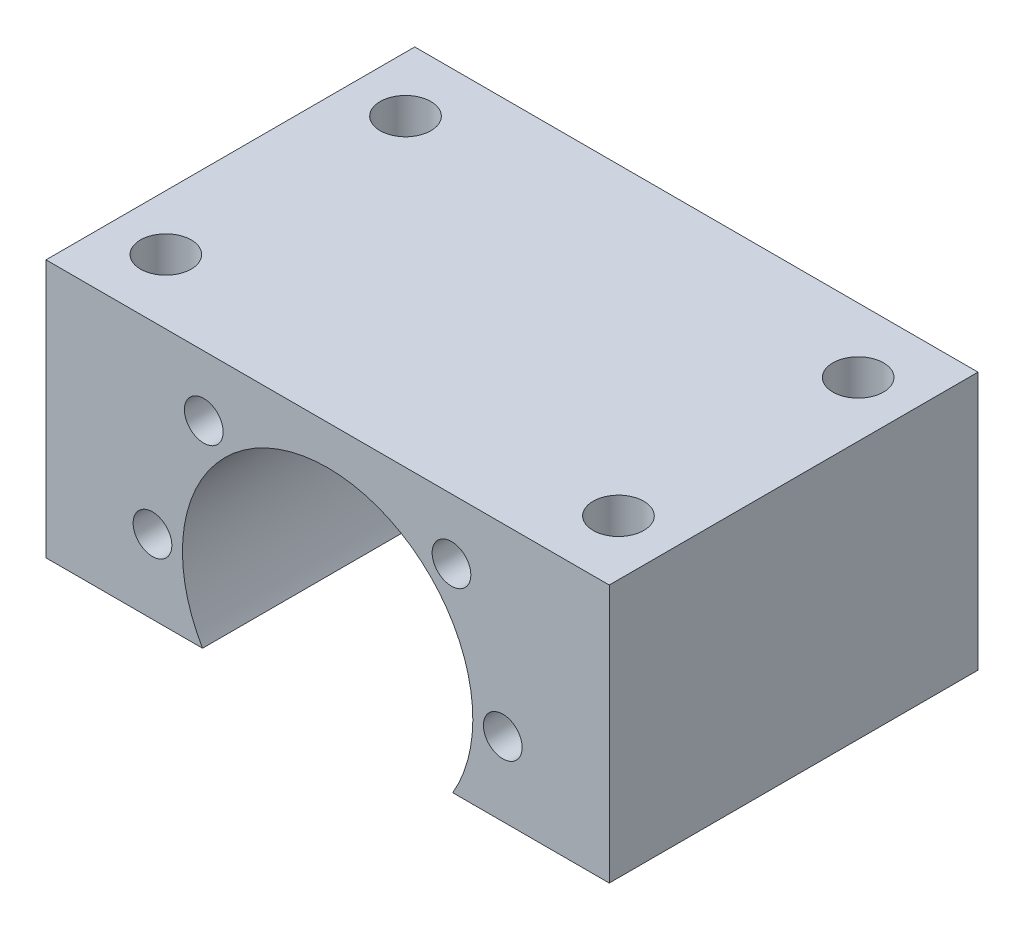
SolidWorks part; units mm, degrees
ref_plane "Front Plane" through (0, 0, 0) normal (0, 0, 1) x (1, 0, 0)
ref_plane "Top Plane" through (0, 0, 0) normal (0, 1, 0) x (1, 0, 0)
ref_plane "Right Plane" through (0, 0, 0) normal (1, 0, 0) x (0, 0, -1)
sketch "Sketch1" plane through (0, 0, 0) normal (0, 0, 1) x (1, 0, 0)
  line L0 (13.2665, 40) -> (-13.2665, 40) construction
  line L1 (13.2665, 40) -> (-13.2665, 40)
  line L4 (27.55, 40) -> (13.2665, 40)
  line L5 (-27.55, 12) -> (-30.55, 12)
  line L7 (-27.55, 40) -> (-13.2665, 40)
  line L9 (-30.55, 12) -> (-30.55, 40)
  line L10 (-27.55, 12) -> (-13.567, 12)
  line L11 (27.55, 12) -> (13.567, 12)
  line L12 (-30.55, 40) -> (-27.55, 40)
  line L13 (27.55, 40) -> (30.55, 40)
  line L14 (30.55, 40) -> (30.55, 12)
  line L15 (30.55, 12) -> (27.55, 12)
  circle A3 centre (-13.435, 33.435) radius 2.1
  circle A7 centre (19, 20) radius 2.1
  circle A8 centre (13.435, 33.435) radius 2.1
  circle A9 centre (-19, 20) radius 2.1
  arc A11 (13.567, 12) -> (-13.567, 12) centre (0, 20) ccw
extrude "Boss-Extrude1" add sketch "Sketch1" against normal up to surface (40 mm away)
sketch "Sketch2" plane through (0, 40, 0) normal (0, 1, 0) x (1, 0, 0)
  circle A0 centre (-24.55, 7) radius 2.75
  circle A1 centre (-24.55, 33) radius 2.75
  circle A2 centre (24.55, 33) radius 2.75
  circle A3 centre (24.55, 7) radius 2.75
extrude "Cut-Extrude1" cut sketch "Sketch2" against normal blind 50 contours A1 | A0 | A3 | A2
